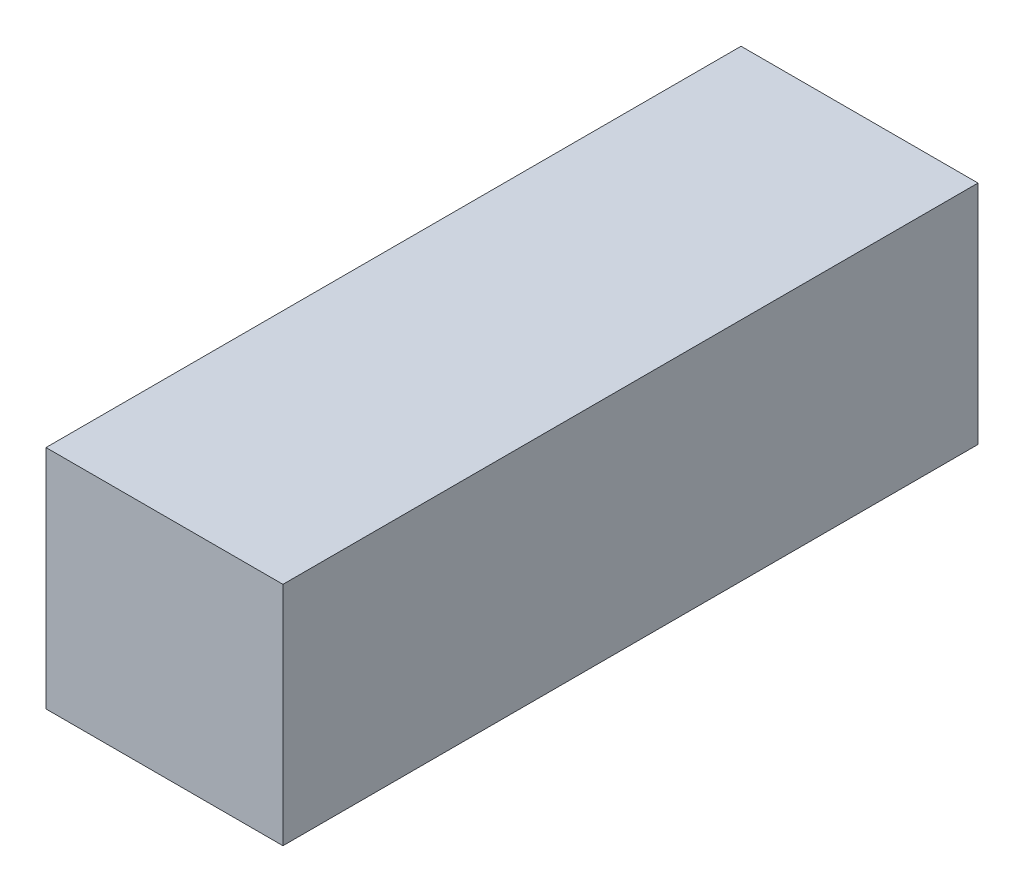
SolidWorks part; units mm, degrees
material "3.0205 (EN-AW 1200)"
ref_plane "Ön Düzlem" through (0, 0, 0) normal (0, 0, 1) x (1, 0, 0)
ref_plane "Üst Düzlem" through (0, 0, 0) normal (0, 1, 0) x (1, 0, 0)
ref_plane "Sağ Düzlem" through (0, 0, 0) normal (1, 0, 0) x (0, 0, -1)
sketch "Çizim1" plane through (0, 0, 0) normal (0, 0, 1) x (1, 0, 0)
  line L1 (-22.5, 21.5) -> (22.5, 21.5)
  line L2 (-22.5, 21.5) -> (-22.5, -21.5)
  line L3 (-22.5, -21.5) -> (22.5, -21.5)
  line L4 (22.5, 21.5) -> (22.5, -21.5)
  dimension "D1" = 45
  dimension "D2" = 43
  dimension "D3" = 21.5
  dimension "D4" = 22.5
extrude "Yükseklik-Ekstrüzyon1" add sketch "Çizim1" along normal blind 132
